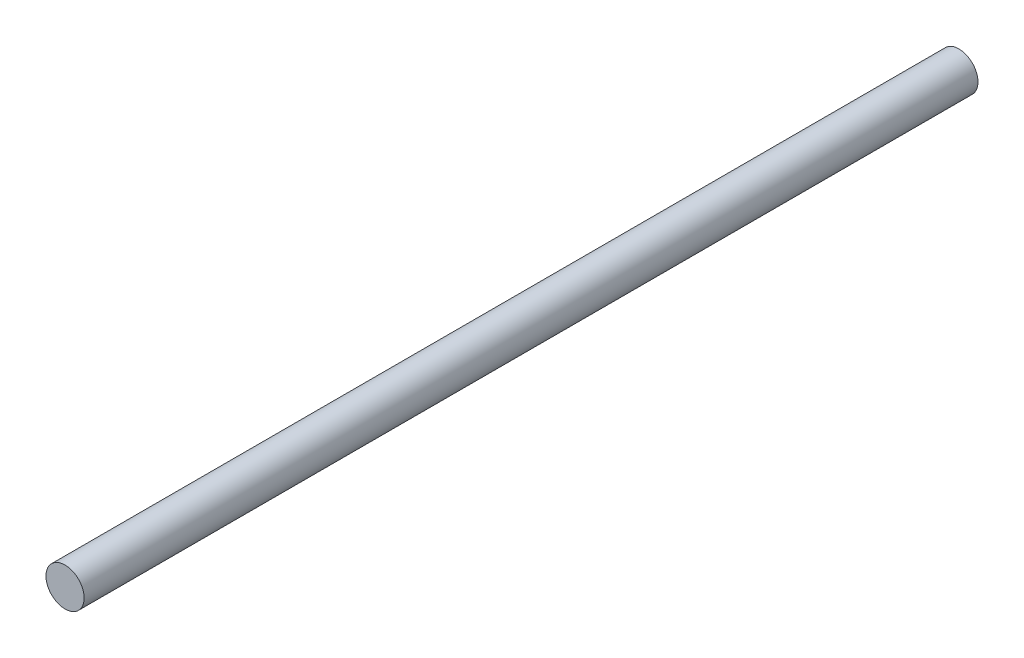
SolidWorks part; units mm, degrees
ref_plane "Front Plane" through (0, 0, 0) normal (0, 0, 1) x (1, 0, 0)
ref_plane "Top Plane" through (0, 0, 0) normal (0, 1, 0) x (1, 0, 0)
ref_plane "Right Plane" through (0, 0, 0) normal (1, 0, 0) x (0, 0, -1)
sketch "Sketch1" plane through (0, 0, 0) normal (0, 0, 1) x (1, 0, 0)
  circle A0 centre (0, 0) radius 3.25
extrude "Boss-Extrude1" add sketch "Sketch1" along normal blind 152.24 contours A0
